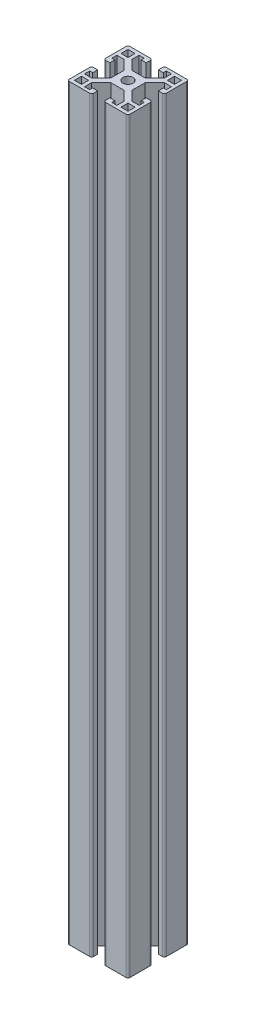
SolidWorks part; units mm, degrees
material "1060 Alloy"
ref_plane "Front Plane" through (0, 0, 0) normal (0, 0, 1) x (1, 0, 0)
ref_plane "Top Plane" through (0, 0, 0) normal (0, 1, 0) x (1, 0, 0)
ref_plane "Right Plane" through (0, 0, 0) normal (1, 0, 0) x (0, 0, -1)
sketch "Sketch1" plane through (0, 0, 0) normal (0, 1, 0) x (1, 0, 0)
  line L0 (-15, 7.5) -> (-15, -4.5)
  line L1 (-15, 7.5) -> (15, 7.5) construction
  line L2 (-15, 7.5) -> (-15, -7.5) construction
  line L3 (-15, -7.5) -> (15, -7.5) construction
  line L4 (15, 7.5) -> (15, -7.5) construction
  line L5 (0, -7.5) -> (0, 7.5) construction
  line L6 (-15, 0) -> (15, 0) construction
  line L7 (-15, 7.5) -> (-3, 7.5)
  line L8 (-15, -4.5) -> (-12, -4.5)
  line L9 (-12, -4.5) -> (-12, -2)
  line L10 (-12, -2) -> (-13.5, -2)
  line L11 (-13.5, -2) -> (-13.5, 0.5)
  line L12 (-13.5, 0.5) -> (-10, 0.5)
  line L13 (-5.25, -2.25) -> (5.25, -2.25) construction
  line L14 (-5.25, -2.25) -> (-5.25, -12.75) construction
  line L15 (-5.25, -12.75) -> (5.25, -12.75) construction
  line L16 (5.25, -2.25) -> (5.25, -12.75) construction
  line L17 (0, -12.75) -> (0, -2.25) construction
  line L18 (-5.25, -7.5) -> (5.25, -7.5) construction
  line L19 (-2.5857, -4.9143) -> (-15, 7.5) construction
  line L20 (-10, 0.5) -> (-5.25, -4.25)
  line L21 (-8, 2.5) -> (-3.25, -2.25)
  line L22 (-3, 7.5) -> (-3, 4.5)
  line L23 (-3, 4.5) -> (-5.5, 4.5)
  line L24 (-5.5, 4.5) -> (-5.5, 6)
  line L25 (-5.5, 6) -> (-8, 6)
  line L26 (-8, 6) -> (-8, 2.5)
  line L27 (5.5, 4.5) -> (5.5, 6)
  line L28 (-13.25, 5.75) -> (-9.75, 5.75)
  line L29 (-13.25, 5.75) -> (-13.25, 2.25)
  line L30 (-13.25, 2.25) -> (-9.75, 2.25)
  line L31 (-9.75, 5.75) -> (-9.75, 2.25)
  line L32 (-11.5, 2.25) -> (-11.5, 5.75) construction
  line L33 (-13.25, 4) -> (-9.75, 4) construction
  line L34 (13.25, 2.25) -> (9.75, 2.25)
  line L35 (13.25, 5.75) -> (13.25, 2.25)
  line L36 (13.25, 5.75) -> (9.75, 5.75)
  line L37 (9.75, 5.75) -> (9.75, 2.25)
  line L38 (3, 4.5) -> (5.5, 4.5)
  line L39 (3, 7.5) -> (3, 4.5)
  line L40 (5.5, 6) -> (8, 6)
  line L41 (8, 6) -> (8, 2.5)
  line L42 (15, 7.5) -> (3, 7.5)
  line L43 (13.5, 0.5) -> (10, 0.5)
  line L44 (13.5, -2) -> (13.5, 0.5)
  line L45 (12, -2) -> (13.5, -2)
  line L46 (15, 7.5) -> (15, -4.5)
  line L47 (15, -4.5) -> (12, -4.5)
  line L48 (12, -4.5) -> (12, -2)
  line L49 (8, 2.5) -> (3.25, -2.25)
  line L50 (10, 0.5) -> (5.25, -4.25)
  line L51 (-5.25, -4.25) -> (-5.25, -10.75)
  line L52 (-3.25, -2.25) -> (3.25, -2.25)
  line L53 (5.25, -4.25) -> (5.25, -10.75)
  line L54 (15, -22.5) -> (15, -10.5)
  line L55 (15, -10.5) -> (12, -10.5)
  line L56 (12, -10.5) -> (12, -13)
  line L57 (12, -13) -> (13.5, -13)
  line L58 (13.5, -13) -> (13.5, -15.5)
  line L59 (13.5, -15.5) -> (10, -15.5)
  line L60 (13.25, -17.25) -> (9.75, -17.25)
  line L61 (13.25, -20.75) -> (13.25, -17.25)
  line L62 (13.25, -20.75) -> (9.75, -20.75)
  line L63 (9.75, -20.75) -> (9.75, -17.25)
  line L64 (8, -21) -> (8, -17.5)
  line L65 (5.5, -21) -> (8, -21)
  line L66 (5.5, -19.5) -> (5.5, -21)
  line L67 (15, -22.5) -> (3, -22.5)
  line L68 (3, -22.5) -> (3, -19.5)
  line L69 (3, -19.5) -> (5.5, -19.5)
  line L70 (10, -15.5) -> (5.25, -10.75)
  line L71 (8, -17.5) -> (3.25, -12.75)
  line L72 (-3, -22.5) -> (-3, -19.5)
  line L73 (-3, -19.5) -> (-5.5, -19.5)
  line L74 (-5.5, -19.5) -> (-5.5, -21)
  line L75 (-5.5, -21) -> (-8, -21)
  line L76 (-8, -21) -> (-8, -17.5)
  line L77 (-15, -22.5) -> (-3, -22.5)
  line L78 (-9.75, -20.75) -> (-9.75, -17.25)
  line L79 (-13.25, -20.75) -> (-9.75, -20.75)
  line L80 (-13.25, -20.75) -> (-13.25, -17.25)
  line L81 (-13.25, -17.25) -> (-9.75, -17.25)
  line L82 (-13.5, -15.5) -> (-10, -15.5)
  line L83 (-13.5, -13) -> (-13.5, -15.5)
  line L84 (-12, -13) -> (-13.5, -13)
  line L85 (-15, -22.5) -> (-15, -10.5)
  line L86 (-15, -10.5) -> (-12, -10.5)
  line L87 (-12, -10.5) -> (-12, -13)
  line L88 (-3.25, -12.75) -> (3.25, -12.75)
  line L89 (-8, -17.5) -> (-3.25, -12.75)
  line L90 (-10, -15.5) -> (-5.25, -10.75)
  circle A0 centre (0, -7.5) radius 2.5
  point P0 (0, 0)
  point P18 (-11.5, 4)
  dimension "D7" = 1.5
  dimension "D19" = 5
  dimension "D1" = 30
  dimension "D2" = 15
  dimension "D3" = 12
  dimension "D4" = 12
  dimension "D5" = 3
  dimension "D6" = 2.5
  dimension "D8" = 2.5
  dimension "D9" = 10.5
  dimension "D10" = 3.5
  dimension "D11" = 45
  dimension "D12" = 3
  dimension "D13" = 2.5
  dimension "D14" = 1.5
  dimension "D15" = 2.5
  dimension "D16" = 3.5
  dimension "D17" = 3.5
  dimension "D18" = 3.5
extrude "Boss-Extrude1" add sketch "Sketch1" against normal blind 370
fillet "Fillet1" radius 1 12 edges at (-3, -185, -7.5) (-15, -185, -7.5) (-15, -185, 4.5) (3, -185, -7.5) (15, -185, -7.5) (15, -185, 4.5) (15, -185, 10.5) (15, -185, 22.5) (3, -185, 22.5) (-15, -185, 10.5) (-3, -185, 22.5) (-15, -185, 22.5)
